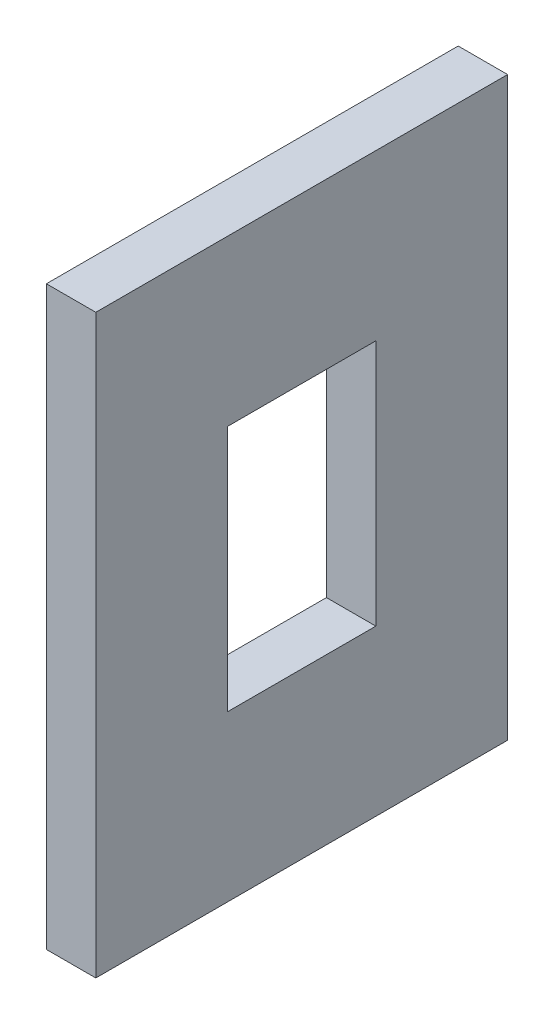
SolidWorks part; units mm, degrees
material "Acrylic (Medium-high impact)"
ref_plane "Front Plane" through (0, 0, 0) normal (0, 0, 1) x (1, 0, 0)
ref_plane "Top Plane" through (0, 0, 0) normal (0, 1, 0) x (1, 0, 0)
ref_plane "Right Plane" through (0, 0, 0) normal (1, 0, 0) x (0, 0, -1)
sketch "Sketch1" plane through (0, 0, 0) normal (1, 0, 0) x (0, 0, -1)
  line L1 (-25, 35) -> (25, 35)
  line L2 (-25, 35) -> (-25, -35)
  line L3 (-25, -35) -> (25, -35)
  line L4 (25, 35) -> (25, -35)
  line L5 (-25, 35) -> (25, -35) construction
  line L6 (-25, -35) -> (25, 35) construction
  point P0 (0, 0)
  dimension "D1" = 70
  dimension "D2" = 50
extrude "Boss-Extrude1" add sketch "Sketch1" along normal blind 6 contours L1 L4 L3 L2
sketch "Sketch2" plane through (6, 0, 0) normal (1, 0, 0) x (0, 0, -1)
  line L0 (-25, 35) -> (25, 35) construction
  line L1 (-9, 15) -> (9, 15)
  line L2 (-9, 15) -> (-9, -15)
  line L3 (-9, -15) -> (9, -15)
  line L4 (9, 15) -> (9, -15)
  line L5 (-9, 15) -> (9, -15) construction
  line L6 (-9, -15) -> (9, 15) construction
  line L7 (-25, 35) -> (-25, -35) construction
  point P0 (0, 0)
  dimension "D1" = 20
  dimension "D2" = 16
extrude "Cut-Extrude1" cut sketch "Sketch2" against normal blind 6
